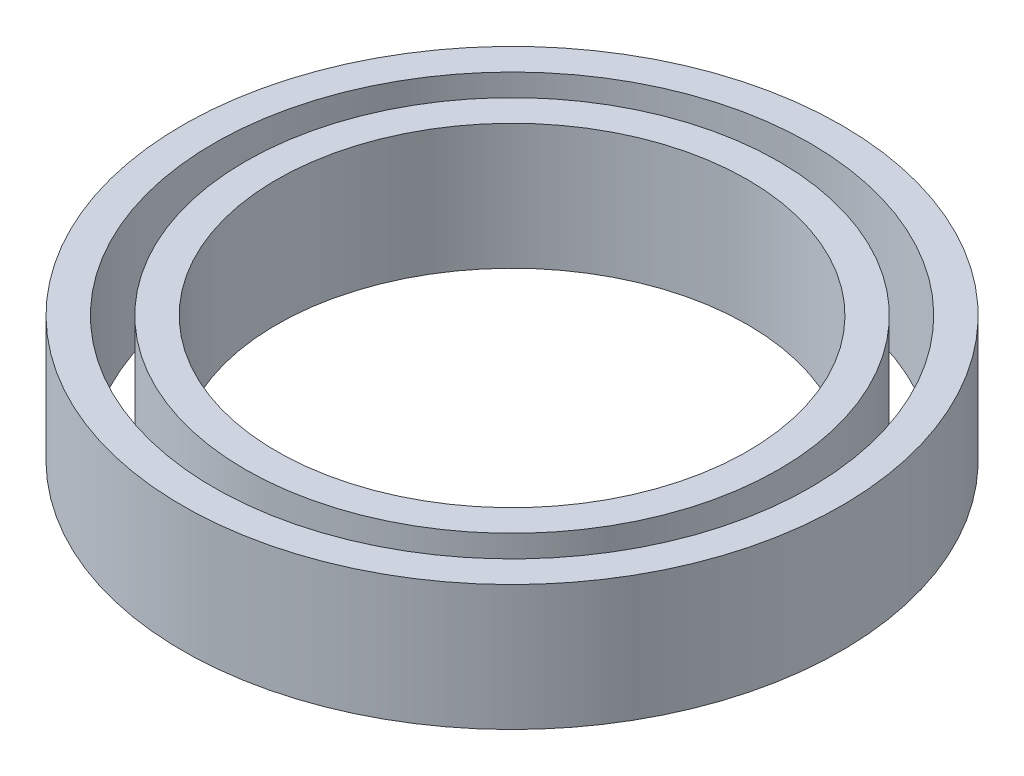
SolidWorks part; units mm, degrees
ref_plane "Plan de face" through (0, 0, 0) normal (0, 0, 1) x (1, 0, 0)
ref_plane "Plan de dessus" through (0, 0, 0) normal (0, 1, 0) x (1, 0, 0)
ref_plane "Plan de droite" through (0, 0, 0) normal (1, 0, 0) x (0, 0, -1)
sketch "Esquisse2" plane through (0, 0, 0) normal (0, 0, 1) x (1, 0, 0)
  line L0 (0, 0) -> (0, 8.4959) construction
  line L1 (7.5, 0) -> (8.5, 0)
  line L2 (7.5, 0) -> (7.5, 4)
  line L3 (7.5, 4) -> (8.5, 4)
  line L4 (8.5, 0) -> (8.5, 4)
  line L5 (9.5, 0) -> (10.5, 0)
  line L6 (9.5, 0) -> (9.5, 4)
  line L7 (9.5, 4) -> (10.5, 4)
  line L8 (10.5, 0) -> (10.5, 4)
  dimension "D1" = 7.5
  dimension "D2" = 10.5
  dimension "D3" = 4
  dimension "D4" = 4
  dimension "D5" = 1
  dimension "D6" = 1
revolve "Révolution1" add sketch "Esquisse2" angle 360 about L0
